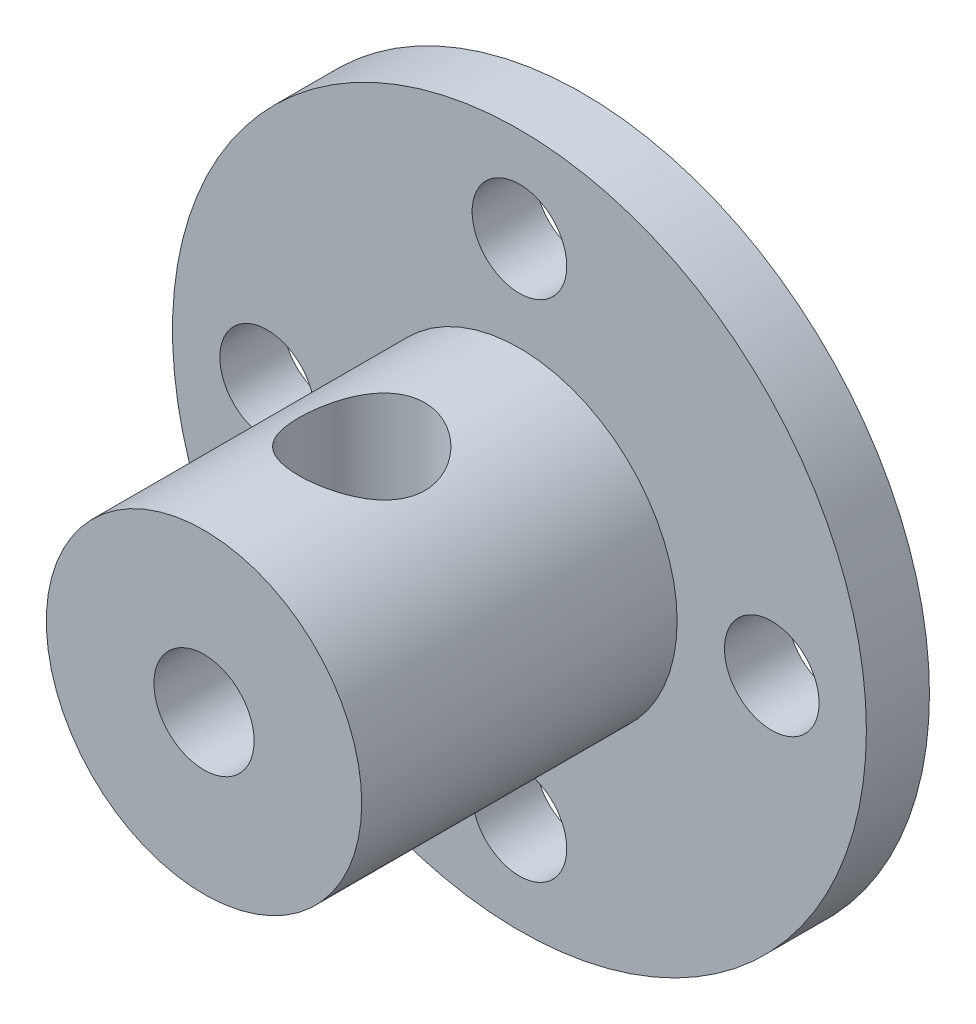
SolidWorks part; units mm, degrees
other "Markup1"
sketch "Sketch5" plane through (16, 16, 13) normal (0.1539, 0.7537, 0.639) x (0.5798, 0.4547, -0.6761)
ref_plane "Front Plane" through (0, 0, 0) normal (0, 0, 1) x (1, 0, 0)
ref_plane "Top Plane" through (0, 0, 0) normal (0, 1, 0) x (1, 0, 0)
ref_plane "Right Plane" through (0, 0, 0) normal (1, 0, 0) x (0, 0, -1)
sketch "Sketch1" plane through (0, 0, 0) normal (0, 0, 1) x (1, 0, 0)
  circle A0 centre (0, 0) radius 11
  dimension "D1" = 22
extrude "Boss-Extrude1" add sketch "Sketch1" along normal blind 2
sketch "Sketch2" plane through (0, 0, 2) normal (0, 0, 1) x (1, 0, 0)
  circle A0 centre (0, 0) radius 5
  circle A1 centre (0, 0) radius 1.5875
  dimension "D1" = 3.175
  dimension "D2" = 10
extrude "Boss-Extrude2" add sketch "Sketch2" along normal blind 10
sketch "Sketch3" plane through (0, 0, 2) normal (0, 0, 1) x (1, 0, 0)
  line L0 (0, 0) -> (0, 8) construction
  line L1 (-8, 0) -> (0, 0) construction
  line L2 (8, 0) -> (0, 0) construction
  line L3 (0, 0) -> (0, -8) construction
  circle A0 centre (0, 8) radius 1.5
  circle A4 centre (8, 0) radius 1.5
  circle A5 centre (0, -8) radius 1.5
  circle A6 centre (-8, 0) radius 1.5
  dimension "D2" = 3
  dimension "D3" = 8
  dimension "D4" = 3
  dimension "D5" = 3
  dimension "D6" = 8
  dimension "D7" = 8
  dimension "D8" = 3
  dimension "D1" = 8
extrude "Cut-Extrude1" cut sketch "Sketch3" against normal through all
sketch "Sketch4" plane through (0, 0, 0) normal (0, 1, 0) x (1, 0, 0)
  line L0 (-5, -12) -> (5, -12) construction
  line L1 (5, -12) -> (5, -2) construction
  circle A0 centre (0, -7) radius 2
  dimension "D1" = 5
  dimension "D2" = 4
  dimension "D3" = 5
extrude "Cut-Extrude2" cut sketch "Sketch4" against normal through all both and the other way through all
